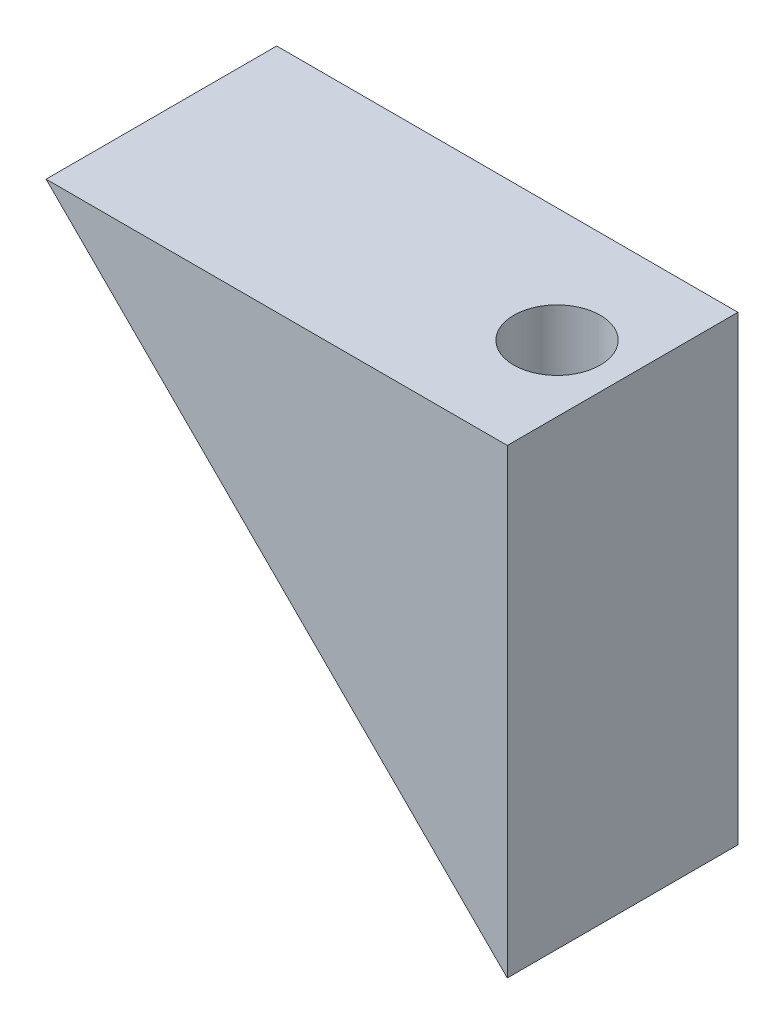
SolidWorks part; units mm, degrees
ref_plane "Front Plane" through (0, 0, 0) normal (0, 0, 1) x (1, 0, 0)
ref_plane "Top Plane" through (0, 0, 0) normal (0, 1, 0) x (1, 0, 0)
ref_plane "Right Plane" through (0, 0, 0) normal (1, 0, 0) x (0, 0, -1)
sketch "Sketch1" plane through (0, 0, 0) normal (0, 0, 1) x (1, 0, 0)
  line L0 (80, -80) -> (-80, 80)
  line L1 (-80, 80) -> (80, 80)
  line L2 (-80, 80) -> (-80, -80)
  line L3 (-80, -80) -> (80, -80)
  line L4 (80, 80) -> (80, -80)
  line L5 (0, -80) -> (0, 80) construction
  line L6 (-80, 0) -> (80, 0) construction
  point P0 (0, 0)
  dimension "D1" = 160
extrude "Boss-Extrude1" add sketch "Sketch1" along normal blind 80 contours L4 L1 L0
sketch "Sketch2" plane through (0, 80, 0) normal (0, 1, 0) x (1, 0, 0)
  line L0 (80, -80) -> (80, 0) construction
  circle A0 centre (57, -39.75) radius 15
  dimension "D1" = 30
  dimension "D2" = 23
extrude "Cut-Extrude1" cut sketch "Sketch2" against normal blind 35
sketch "Sketch3" plane through (0, 45, 0) normal (0, 1, 0) x (1, 0, 0)
  circle A0 centre (57, -39.75) radius 9.75
  dimension "D1" = 19.5
extrude "Cut-Extrude2" cut sketch "Sketch3" against normal blind 120 from surface at 35 starting at face at (57, 80, 54.75)
